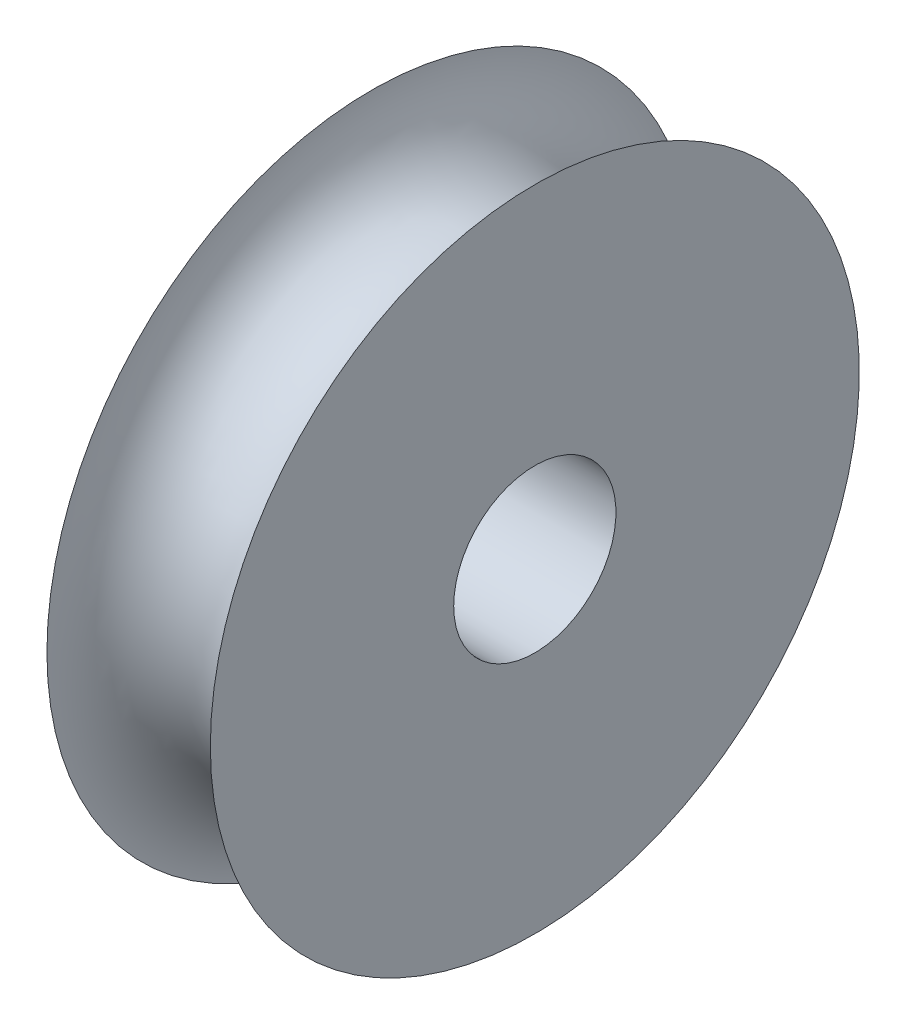
SolidWorks part; units mm, degrees
ref_plane "Front Plane" through (0, 0, 0) normal (0, 0, 1) x (1, 0, 0)
ref_plane "Top Plane" through (0, 0, 0) normal (0, 1, 0) x (1, 0, 0)
ref_plane "Right Plane" through (0, 0, 0) normal (1, 0, 0) x (0, 0, -1)
sketch "Sketch1" plane through (0, 0, 0) normal (1, 0, 0) x (0, 0, -1)
  circle A0 centre (0, 0) radius 25.4
  circle A1 centre (0, 0) radius 6.35
sketch "Sketch3" plane through (0, 0, 0) normal (0, 0, 1) x (1, 0, 0)
  line L0 (0, -25.4) -> (0, 25.4) construction
  line L1 (0, 25.4) -> (0, 6.35)
  line L2 (12.7913, 25.4) -> (12.7913, 6.35)
  line L3 (12.7913, 6.35) -> (0, 6.35)
  line L4 (0, -6.35) -> (0, 6.35) construction
  arc A0 (0, 25.4) -> (12.7913, 25.4) centre (6.3956, 25.4) ccw
sweep "Sweep2" add profiles "Sketch3" path "Sketch1"
